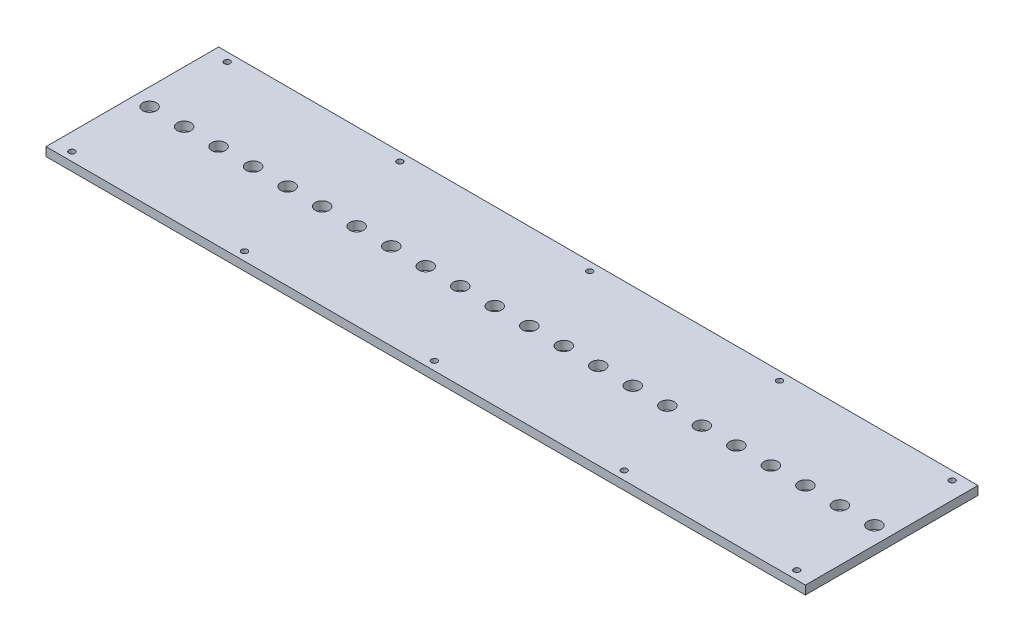
SolidWorks part; units mm, degrees
ref_plane "Front Plane" through (0, 0, 0) normal (0, 0, 1) x (1, 0, 0)
ref_plane "Top Plane" through (0, 0, 0) normal (0, 1, 0) x (1, 0, 0)
ref_plane "Right Plane" through (0, 0, 0) normal (1, 0, 0) x (0, 0, -1)
sketch "Sketch2" plane through (0, 0, 0) normal (0, 1, 0) x (1, 0, 0)
  line L0 (0, 0) -> (0, 127)
  line L1 (0, 127) -> (558.8, 127)
  line L2 (558.8, 127) -> (558.8, 0)
  line L3 (558.8, 0) -> (0, 0)
  circle A0 centre (12.7, 63.5) radius 5.08
  circle A1 centre (38.1, 63.5) radius 5.08
  circle A2 centre (63.5, 63.5) radius 5.08
  circle A3 centre (88.9, 63.5) radius 5.08
  circle A4 centre (114.3, 63.5) radius 5.08
  circle A5 centre (139.7, 63.5) radius 5.08
  circle A6 centre (165.1, 63.5) radius 5.08
  circle A7 centre (190.5, 63.5) radius 5.08
  circle A8 centre (215.9, 63.5) radius 5.08
  circle A9 centre (241.3, 63.5) radius 5.08
  circle A10 centre (266.7, 63.5) radius 5.08
  circle A11 centre (292.1, 63.5) radius 5.08
  circle A12 centre (317.5, 63.5) radius 5.08
  circle A13 centre (342.9, 63.5) radius 5.08
  circle A14 centre (368.3, 63.5) radius 5.08
  circle A15 centre (393.7, 63.5) radius 5.08
  circle A16 centre (419.1, 63.5) radius 5.08
  circle A17 centre (444.5, 63.5) radius 5.08
  circle A18 centre (469.9, 63.5) radius 5.08
  circle A19 centre (495.3, 63.5) radius 5.08
  circle A20 centre (520.7, 63.5) radius 5.08
  circle A21 centre (546.1, 63.5) radius 5.08
  dimension "D3" = 12.7
  dimension "D1" = 127
  dimension "D2" = 558.8
  dimension "D4" = 22
extrude "Boss-Extrude1" add sketch "Sketch2" along normal blind 6.35
sketch "Sketch3" plane through (0, 6.35, 0) normal (0, 1, 0) x (1, 0, 0)
  line L1 (12.7, 120.65) -> (546.1, 120.65) construction
  line L2 (546.1, 120.65) -> (546.1, 6.35) construction
  line L3 (546.1, 6.35) -> (12.7, 6.35) construction
  line L4 (12.7, 6.35) -> (12.7, 120.65) construction
  line L5 (139.7, 120.65) -> (139.7, 6.35) construction
  line L6 (279.4, 120.65) -> (279.4, 6.35) construction
  line L7 (419.1, 120.65) -> (419.1, 6.35) construction
  line L8 (0, 127) -> (0, 0) construction
  line L9 (0, 0) -> (558.8, 0) construction
  circle A0 centre (12.7, 120.65) radius 2.1828
  circle A1 centre (139.7, 120.65) radius 2.1828
  circle A2 centre (279.4, 120.65) radius 2.1828
  circle A3 centre (419.1, 120.65) radius 2.1828
  circle A4 centre (546.1, 120.65) radius 2.1828
  circle A5 centre (546.1, 6.35) radius 2.1828
  circle A6 centre (419.1, 6.35) radius 2.1828
  circle A7 centre (279.4, 6.35) radius 2.1828
  circle A8 centre (139.7, 6.35) radius 2.1828
  circle A9 centre (12.7, 6.35) radius 2.1828
  dimension "D1" = 12.7
  dimension "D8" = 4.3656
  dimension "D2" = 6.35
  dimension "D3" = 120.65
  dimension "D4" = 546.1
  dimension "D5" = 139.7
  dimension "D6" = 279.4
  dimension "D7" = 419.1
extrude "Cut-Extrude1" cut sketch "Sketch3" against normal up to surface (6.35 mm away) up to face at (520.7, 0, -58.42)
